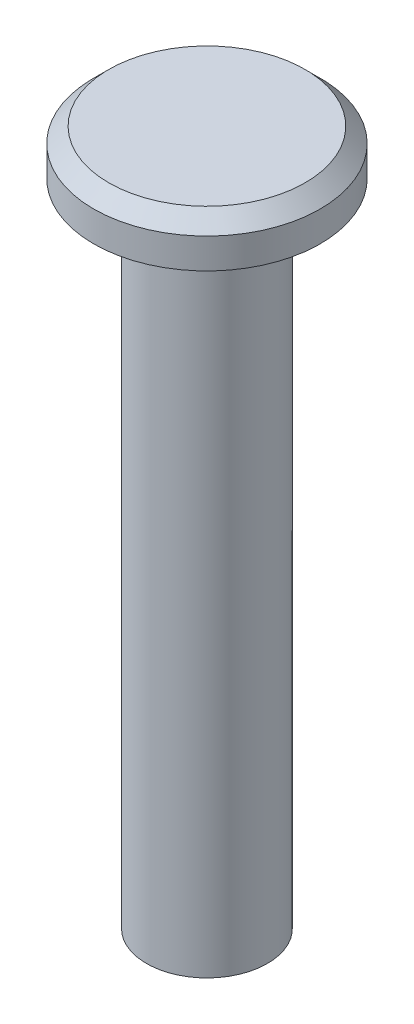
SolidWorks part; units mm, degrees
ref_plane "Front Plane" through (0, 0, 0) normal (0, 0, 1) x (1, 0, 0)
ref_plane "Top Plane" through (0, 0, 0) normal (0, 1, 0) x (1, 0, 0)
ref_plane "Right Plane" through (0, 0, 0) normal (1, 0, 0) x (0, 0, -1)
sketch "Sketch2" plane through (0, 0, 0) normal (0, 1, 0) x (1, 0, 0)
  circle A0 centre (0, 0) radius 7.5
  dimension "D1" = 15
extrude "Boss-Extrude1" add sketch "Sketch2" along normal blind 3
sketch "Sketch3" plane through (0, 0, 0) normal (0, -1, 0) x (1, 0, 0)
  circle A0 centre (0, 0) radius 4
  dimension "D1" = 8
extrude "Boss-Extrude2" add sketch "Sketch3" along normal blind 43
cosmetic thread "Cosmetic Thread1" parameters "D1"=3, "D2"=6.561
chamfer "Chamfer1" distance 1 angle 45 1 edges at (0, 3, 7.5)
